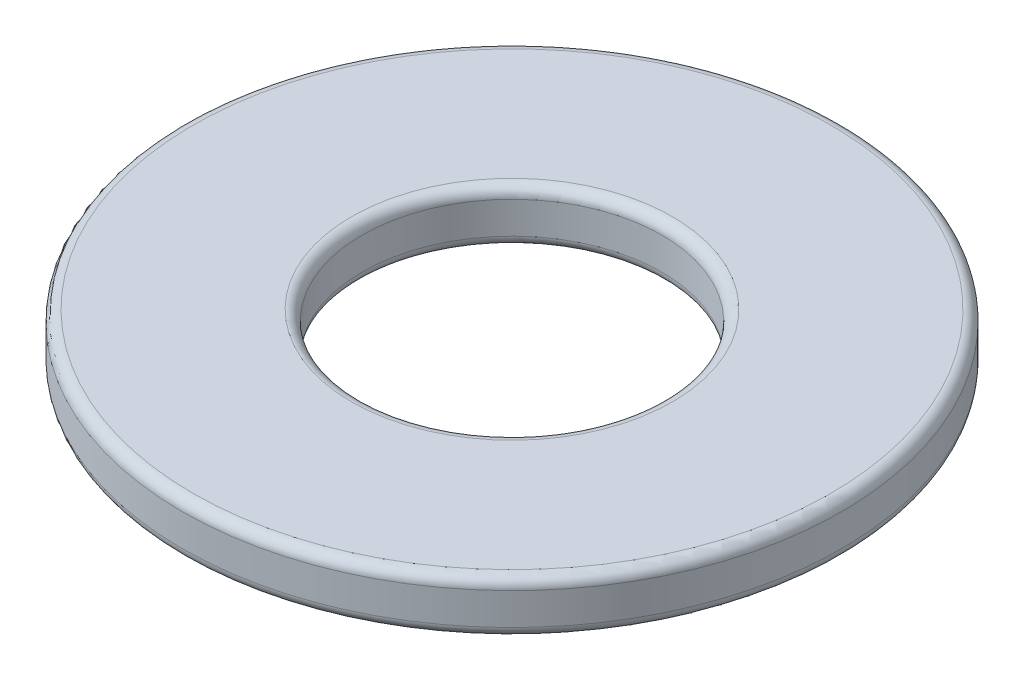
SolidWorks part; units mm, degrees
material "Chrome Stainless Steel"
ref_plane "Front" through (0, 0, 0) normal (0, 0, 1) x (1, 0, 0)
ref_plane "Top" through (0, 0, 0) normal (0, 1, 0) x (1, 0, 0)
ref_plane "Right" through (0, 0, 0) normal (1, 0, 0) x (0, 0, -1)
sketch "Sketch1" plane through (0, 0, 0) normal (0, 1, 0) x (1, 0, 0)
  circle A0 centre (0, 0) radius 2.8575
  circle A1 centre (0, 0) radius 6.2865
  dimension "D1" = 5.715
  dimension "D2" = 12.573
extrude "Extrude1" add sketch "Sketch1" along normal blind 1.016
fillet "Fillet1" radius 0.2032 4 edges at (0, 1.016, 2.8575) (0, 1.016, 6.2865) (0, 0, 2.8575) (0, 0, 6.2865)
